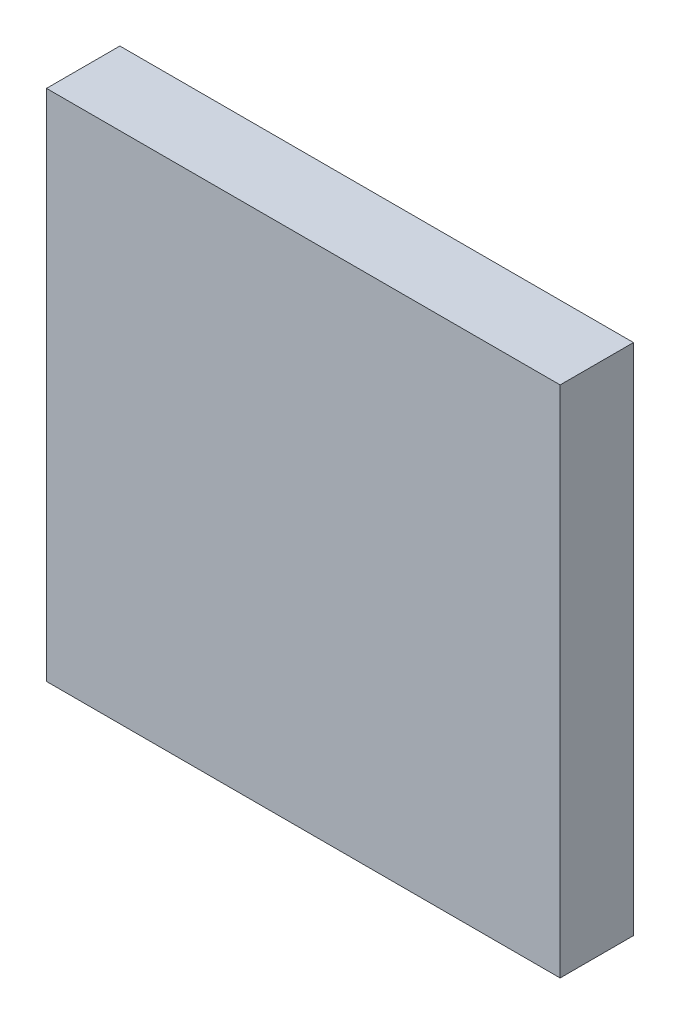
SolidWorks part; units mm, degrees
ref_plane "Front Plane" through (0, 0, 0) normal (0, 0, 1) x (1, 0, 0)
ref_plane "Top Plane" through (0, 0, 0) normal (0, 1, 0) x (1, 0, 0)
ref_plane "Right Plane" through (0, 0, 0) normal (1, 0, 0) x (0, 0, -1)
sketch "Sketch1" plane through (0, 0, 0) normal (0, 0, 1) x (1, 0, 0)
  line L1 (-19.6138, 16.2133) -> (15.3862, 16.2133)
  line L2 (-19.6138, 16.2133) -> (-19.6138, -18.7867)
  line L3 (-19.6138, -18.7867) -> (15.3862, -18.7867)
  line L4 (15.3862, 16.2133) -> (15.3862, -18.7867)
  dimension "D1" = 35
  dimension "D2" = 35
extrude "Boss-Extrude1" add sketch "Sketch1" along normal blind 5
